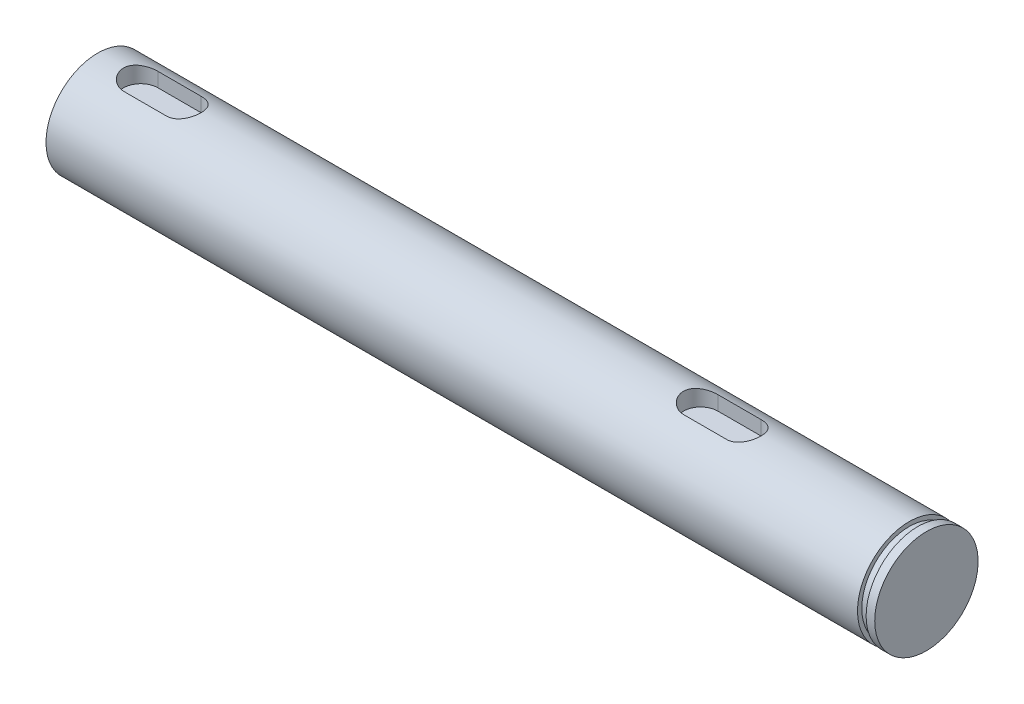
SolidWorks part; units mm, degrees
ref_plane "正面" through (0, 0, 0) normal (0, 0, 1) x (1, 0, 0)
ref_plane "平面" through (0, 0, 0) normal (0, 1, 0) x (1, 0, 0)
ref_plane "右側面" through (0, 0, 0) normal (1, 0, 0) x (0, 0, -1)
sketch "ｽｹｯﾁ2" plane through (0, 0, 0) normal (0, 0, 1) x (1, 0, 0)
  line L1 (0, 0) -> (96.2, 0)
  line L2 (0, 0) -> (0, 6)
  line L3 (0, 6) -> (96.2, 6)
  line L4 (96.2, 0) -> (96.2, 6)
  line L5 (48.1, 6) -> (48.1, 0) construction
  line L6 (0, 3) -> (96.2, 3) construction
  line L7 (1, 6) -> (2, 6)
  line L13 (94.2, 6) -> (95.2, 6)
  line L14 (94.2, 6) -> (94.2, 5.5)
  line L15 (94.2, 5.5) -> (95.2, 5.5)
  line L16 (95.2, 6) -> (95.2, 5.5)
  line L17 (94.7, 5.5) -> (94.7, 6) construction
  line L18 (94.2, 5.75) -> (95.2, 5.75) construction
  point P50 (1.5, 5.75)
  point P64 (48.1, 3)
  point P99 (94.7, 5.75)
  dimension "D1" = 6
  dimension "D2" = 96.2
  dimension "D6" = 1
  dimension "D7" = 1
  dimension "D8" = 0.5
revolve "回転1" add sketch "ｽｹｯﾁ2" angle 360 about L1
ref_plane "平面1" through (0, 6, 0) normal (0, 1, 0) x (1, 0, 0)
sketch "ｽｹｯﾁ4" plane through (0, 6, 0) normal (0, 1, 0) x (1, 0, 0)
  line L0 (5, 0) -> (10, 0) construction
  line L1 (5, 2) -> (10, 2)
  line L2 (5, -2) -> (10, -2)
  line L3 (0, 6) -> (0, -6) construction
  line L4 (75, 0) -> (70, 0) construction
  line L5 (75, -2) -> (70, -2)
  line L6 (75, 2) -> (70, 2)
  arc A0 (5, 2) -> (5, -2) centre (5, 0) ccw
  arc A1 (10, -2) -> (10, 2) centre (10, 0) ccw
  arc A2 (75, -2) -> (75, 2) centre (75, 0) ccw
  arc A3 (70, 2) -> (70, -2) centre (70, 0) ccw
  point P3 (7.5, 0)
  point P12 (72.5, 0)
  dimension "D3" = 2
  dimension "D4" = 2
  dimension "D6" = 70
  dimension "D1" = 5
  dimension "D2" = 5
  dimension "D5" = 5
extrude "ｶｯﾄ - 押し出し1" cut sketch "ｽｹｯﾁ4" against normal blind 2
